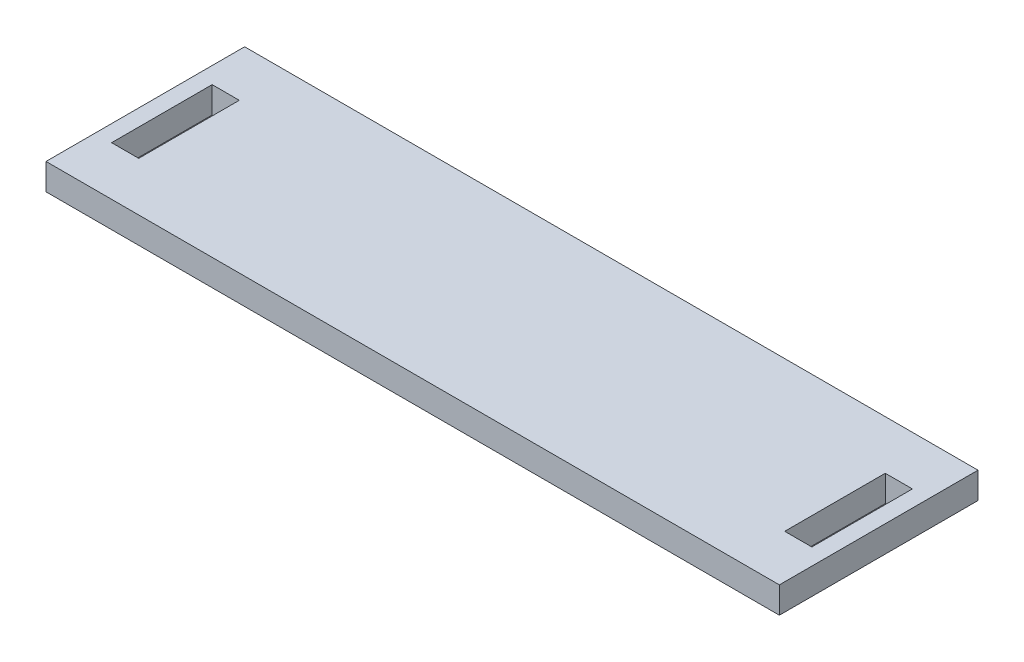
SolidWorks part; units mm, degrees
other "Markup1"
sketch "Sketch8" plane through (-54.8684, 3.18, -6.3861) normal (0, 1, 0) x (1, 0, 0)
ref_plane "Front Plane" through (0, 0, 0) normal (0, 0, 1) x (1, 0, 0)
ref_plane "Top Plane" through (0, 0, 0) normal (0, 1, 0) x (1, 0, 0)
ref_plane "Right Plane" through (0, 0, 0) normal (1, 0, 0) x (0, 0, -1)
sketch "Sketch1" plane through (0, 0, 0) normal (0, 1, 0) x (1, 0, 0)
  line L1 (-55.7884, 6.3861) -> (28.8216, 6.3861)
  line L2 (-55.7884, 6.3861) -> (-55.7884, -17.6139)
  line L3 (-55.7884, -17.6139) -> (28.8216, -17.6139)
  line L4 (28.8216, 6.3861) -> (28.8216, -17.6139)
  dimension "D1" = 84.61
  dimension "D2" = 24
extrude "Boss-Extrude1" add sketch "Sketch1" along normal blind 3.18
ref_plane "Plane1" through (-13.4834, 0, 0) normal (-1, 0, 0) x (0, 0, 1)
sketch "Sketch10" plane through (-55.7884, 0, 0) normal (-1, 0, 0) x (0, 0, 1)
  line L4 (-6.3861, 0) -> (17.6139, 0)
  line L5 (17.6139, 0) -> (17.6139, 3.18)
  line L6 (17.6139, 3.18) -> (-6.3861, 3.18)
  line L7 (-6.3861, 3.18) -> (-6.3861, 0)
  line L8 (-6.3861, 0) -> (17.6139, 0)
  line L9 (17.6139, 0) -> (17.6139, 3.18)
  line L10 (17.6139, 3.18) -> (-6.3861, 3.18)
  line L11 (-6.3861, 3.18) -> (-6.3861, 0)
  dimension "D1" = 0
extrude "Boss-Extrude2" add sketch "Sketch10" along normal blind 2
sketch "Sketch9" plane through (0, 3.18, 0) normal (0, 1, 0) x (1, 0, 0)
  line L1 (-55.7884, 0.4611) -> (-52.5084, 0.4611)
  line L2 (-55.7884, 0.4611) -> (-55.7884, -11.6889)
  line L3 (-55.7884, -11.6889) -> (-52.5084, -11.6889)
  line L4 (-52.5084, 0.4611) -> (-52.5084, -11.6889)
  line L5 (-57.7884, 6.3861) -> (-57.7884, -17.6139) construction
  point P6 (-55.7884, -5.6139)
  point P7 (-57.7884, -5.6139)
  dimension "D1" = 12.15
  dimension "D2" = 3.28
  dimension "D3" = 2
extrude "Cut-Extrude1" cut sketch "Sketch9" against normal through all
mirror "Mirror1" about plane through (-13.4834, 0, 0) normal (-1, 0, 0) of "Cut-Extrude1", "Boss-Extrude2"
equation "\"Width\"= 24mm"
equation "\"D1@Sketch9\"=\"Width\"/2+.15"
equation "\"MaterialThickness\"= 3.18mm"
equation "\"D2@Sketch9\"=\"MaterialThickness\"+0.1"
